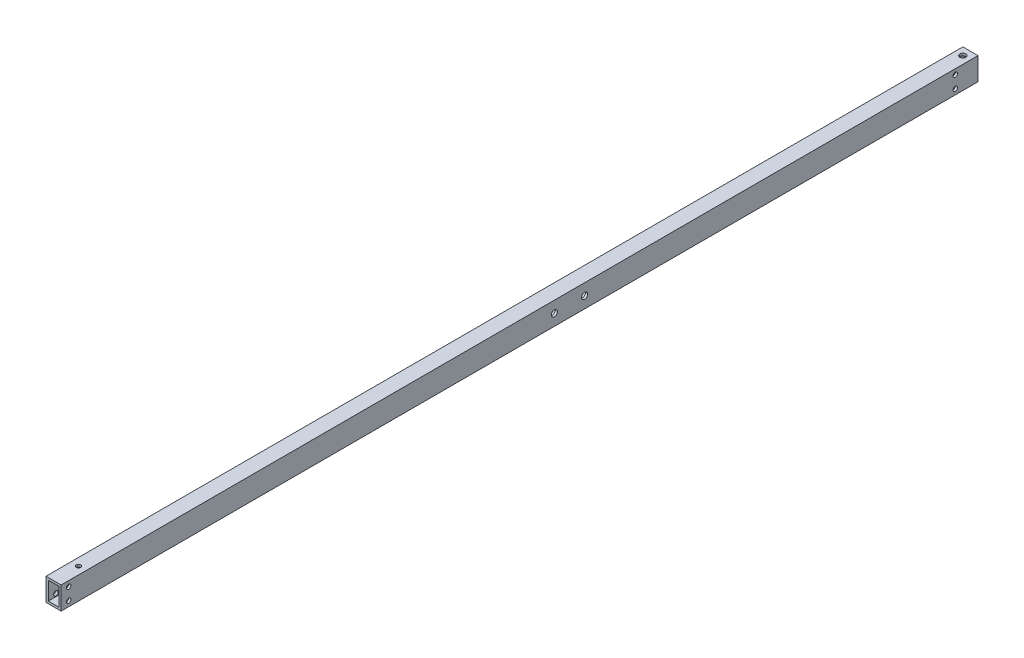
SolidWorks part; units mm, degrees
material "1060 合金"
ref_plane "正面" through (0, 0, 0) normal (0, 0, 1) x (1, 0, 0)
ref_plane "平面" through (0, 0, 0) normal (0, 1, 0) x (1, 0, 0)
ref_plane "右側面" through (0, 0, 0) normal (1, 0, 0) x (0, 0, -1)
sketch "ｽｹｯﾁ1" plane through (0, 0, 0) normal (0, 0, 1) x (1, 0, 0)
  line L1 (-5, -7.5) -> (5, -7.5)
  line L2 (-5, -7.5) -> (-5, 7.5)
  line L3 (-5, 7.5) -> (5, 7.5)
  line L4 (5, -7.5) -> (5, 7.5)
  line L5 (-5, -7.5) -> (5, 7.5) construction
  line L6 (-5, 7.5) -> (5, -7.5) construction
  point P0 (0, 0)
  dimension "D1" = 10
  dimension "D2" = 15
extrude "押し出し-薄板1" add sketch "ｽｹｯﾁ1" along normal blind 606 thin thin type one direction reverse wall 1.5
sketch "ｽｹｯﾁ2" plane through (5, 0, 0) normal (1, 0, 0) x (0, 0, -1)
  line L0 (-328, 0) -> (49672, 0) construction
  line L1 (-606, -7.5) -> (-606, 7.5) construction
  line L2 (-303, 10) -> (-303, 50010) construction
  line L3 (-606, 7.5) -> (0, 7.5) construction
  line L4 (-270, 7.5) -> (-270, -7.5) construction
  line L5 (0, -7.5) -> (0, 7.5) construction
  line L6 (-606, -7.5) -> (0, -7.5) construction
  circle A5 centre (-280, 0) radius 2
  circle A11 centre (-260, 0) radius 2
  circle A12 centre (-15, 4) radius 1.5
  circle A13 centre (-15, -4) radius 1.5
  circle A14 centre (-601, 4) radius 1.5
  circle A15 centre (-601, -4) radius 1.5
  point P4 (-606, 0)
  point P13 (-303, 7.5)
  dimension "D2" = 4
  dimension "D3" = 8
  dimension "D4" = 15
  dimension "D5" = 270
  dimension "D6" = 7.5
  dimension "D7" = 3
  dimension "D8" = 8
  dimension "D9" = 3
  dimension "D10" = 5
  dimension "D11" = 20
extrude "ｶｯﾄ - 押し出し1" cut sketch "ｽｹｯﾁ2" against normal through all
sketch "ｽｹｯﾁ3" plane through (0, 7.5, 0) normal (0, 1, 0) x (1, 0, 0)
  line L0 (0, 0) -> (0, 50000) construction
  line L1 (5, 0) -> (-5, 0) construction
  line L2 (5, -606) -> (-5, -606) construction
  circle A0 centre (0, -5) radius 2
  circle A1 centre (0, -589.5) radius 1.5
  dimension "D1" = 5
  dimension "D2" = 4
  dimension "D3" = 16.5
  dimension "D4" = 3
extrude "ｶｯﾄ - 押し出し2" cut sketch "ｽｹｯﾁ3" against normal through all
